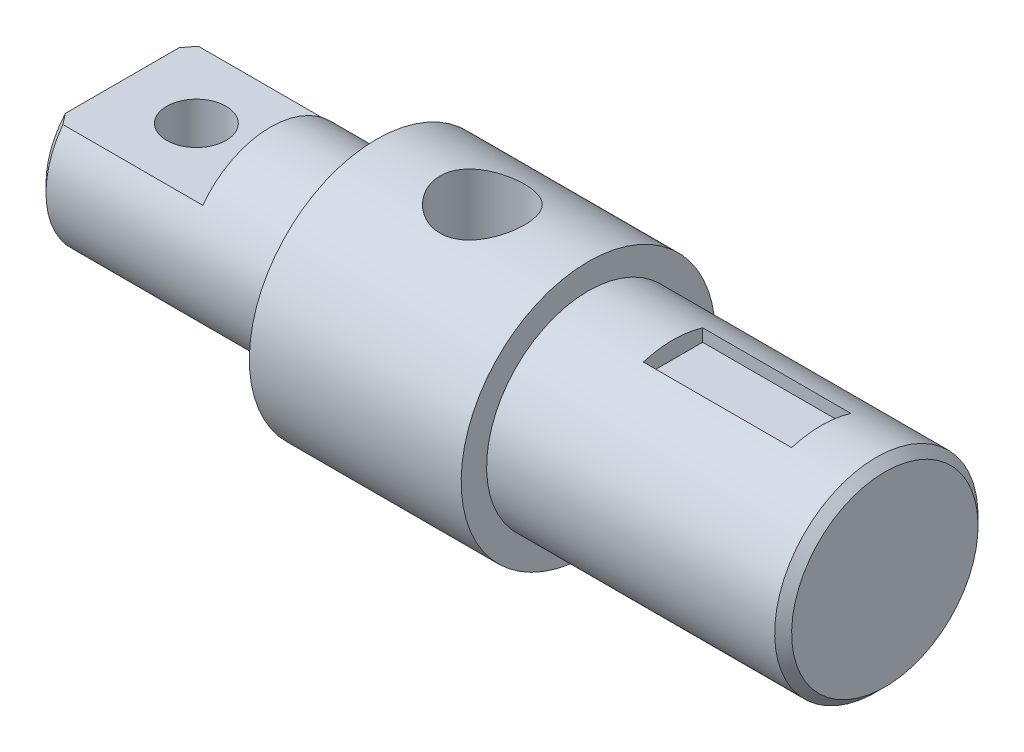
SolidWorks part; units mm, degrees
ref_plane "Спереди" through (0, 0, 0) normal (0, 0, 1) x (1, 0, 0)
ref_plane "Сверху" through (0, 0, 0) normal (0, 1, 0) x (1, 0, 0)
ref_plane "Справа" through (0, 0, 0) normal (1, 0, 0) x (0, 0, -1)
sketch "Эскиз2" plane through (0, 0, 0) normal (0, 0, 1) x (1, 0, 0)
  line L0 (180, 0) -> (0, 0) construction
  line L1 (0, 0) -> (0, 20)
  line L2 (0, 20) -> (60, 20)
  line L3 (60, 20) -> (60, 30)
  line L4 (60, 30) -> (110, 30)
  line L5 (110, 30) -> (110, 24)
  line L6 (110, 24) -> (180, 24)
  line L7 (180, 24) -> (180, 0)
  line L8 (180, 0) -> (0, 0)
  point P3 (223.5449, 0)
  point P11 (223.987, 2.979)
  point P12 (0, 0)
  dimension "D1" = 40
  dimension "D2" = 60
  dimension "D3" = 70
  dimension "D4" = 180
  dimension "D5" = 48
  dimension "D6" = 60
revolve "Повернуть1" add sketch "Эскиз2" angle 360 about L0
sketch "Эскиз3" plane through (0, 0, 0) normal (-1, 0, 0) x (0, 0, 1)
  line L0 (-16, 12) -> (16, 12)
  circle A0 centre (0, 0) radius 20 construction
  circle A3 centre (0, 0) radius 20 construction
  arc A4 (16, 12) -> (-16, 12) centre (0, 0) ccw
  dimension "D1" = 32
extrude "Вырез-Вытянуть1" cut sketch "Эскиз3" against normal blind 35
sketch "Эскиз4" plane through (0, 0, 0) normal (0, 1, 0) x (1, 0, 0)
  line L0 (0, 0) -> (35, 0) construction
  line L1 (0, 16) -> (0, -16) construction
  line L2 (35, 16) -> (35, -16) construction
  line L3 (60, 0) -> (110, 0) construction
  line L6 (110, -24) -> (110, 24) construction
  line L7 (60, 30) -> (60, -30) construction
  circle A0 centre (17.5, 0) radius 7
  circle A1 centre (85, 0) radius 10
  point P14 (60, 0)
  point P16 (32.474, 0)
  point P17 (30.6278, 0)
  point P18 (17.5, 0)
  point P19 (95.1543, 0)
  point P20 (0, 0)
  point P21 (85, 0)
  point P22 (89.4838, 0)
  point P23 (60, 0)
  dimension "D1" = 14
  dimension "D2" = 20
extrude "Вырез-Вытянуть2" cut sketch "Эскиз4" against normal through all both and the other way through all
ref_plane "Плоскость4" through (0, 24, 0) normal (0, 1, 0) x (1, 0, 0)
sketch "Эскиз5" plane through (0, 24, 0) normal (0, 1, 0) x (1, 0, 0)
  line L0 (180, -24) -> (180, 24) construction
  line L1 (130, -7) -> (165, -7)
  line L2 (130, -7) -> (130, 7)
  line L3 (130, 7) -> (165, 7)
  line L4 (165, -7) -> (165, 7)
  line L5 (130, -7) -> (165, 7) construction
  line L6 (130, 7) -> (165, -7) construction
  point P0 (147.5, 0)
  dimension "D1" = 35
  dimension "D2" = 14
  dimension "D3" = 15
extrude "Вырез-Вытянуть3" cut sketch "Эскиз5" against normal blind 4
chamfer "Фаска1" distance 2 angle 45 2 edges at (180, 24, 0) (0, -20, 0)
